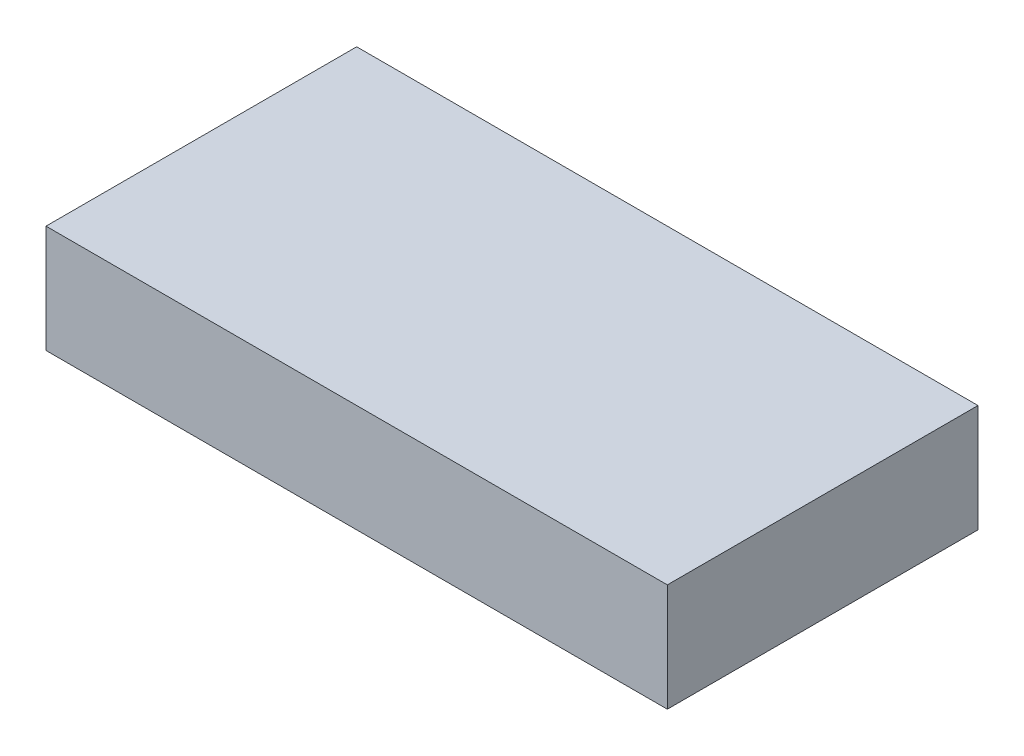
SolidWorks part; units mm, degrees
ref_plane "前视基准面" through (0, 0, 0) normal (0, 0, 1) x (1, 0, 0)
ref_plane "上视基准面" through (0, 0, 0) normal (0, 1, 0) x (1, 0, 0)
ref_plane "右视基准面" through (0, 0, 0) normal (1, 0, 0) x (0, 0, -1)
other "Configuration Table"
sketch "草图1" plane through (0, 0, 0) normal (0, 0, 1) x (1, 0, 0)
  line L1 (-75, -13) -> (75, -13)
  line L2 (-75, -13) -> (-75, 13)
  line L3 (-75, 13) -> (75, 13)
  line L4 (75, -13) -> (75, 13)
extrude "solid_obs_04_left_wall" add sketch "草图1" along normal blind 75
